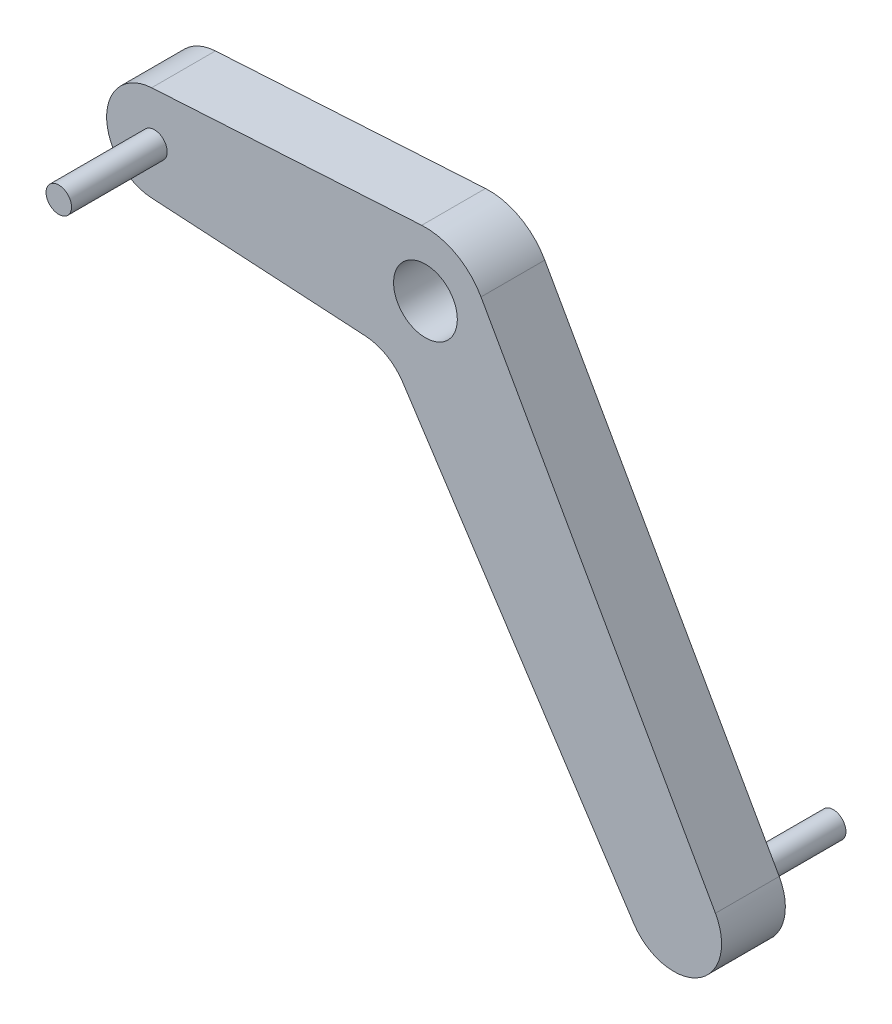
SolidWorks part; units mm, degrees
ref_plane "前视基准面" through (0, 0, 0) normal (0, 0, 1) x (1, 0, 0)
ref_plane "上视基准面" through (0, 0, 0) normal (0, 1, 0) x (1, 0, 0)
ref_plane "右视基准面" through (0, 0, 0) normal (1, 0, 0) x (0, 0, -1)
other "Configuration Table"
sketch "草图1" plane through (0, 0, 0) normal (0, 0, 1) x (1, 0, 0)
  line L0 (-85, 0) -> (0, 0) construction
  line L1 (0, 0) -> (77.8831, -128.196) construction
  line L7 (-1.1765, 19.9654) -> (-85.8824, 14.974)
  line L8 (-85.8824, -14.974) -> (-18.7635, -18.929)
  line L9 (65.3303, -136.4073) -> (-7.093, -25.6918)
  line L10 (17.4295, 9.8089) -> (90.9552, -120.8394)
  arc A5 (17.4295, 9.8089) -> (-1.1765, 19.9654) centre (0, 0) ccw
  arc A6 (-85.8824, 14.974) -> (-85.8824, -14.974) centre (-85, 0) ccw
  arc A7 (65.3303, -136.4073) -> (90.9552, -120.8394) centre (77.8831, -128.196) ccw
  arc A8 (-7.093, -25.6918) -> (-18.7635, -18.929) centre (-19.6458, -33.9031) ccw
  dimension "D1" = 15
extrude "凸台-拉伸1" add sketch "草图1" along normal blind 20
sketch "草图2" plane through (0, 0, 0) normal (0, 0, 1) x (1, 0, 0)
  circle A0 centre (0, 0) radius 10
extrude "切除-拉伸1" cut sketch "草图2" along normal blind 20
sketch "草图6" plane through (0, 0, 20) normal (0, 0, 1) x (1, 0, 0)
  circle A0 centre (-85, 0) radius 4
extrude "凸台-拉伸3" add sketch "草图6" along normal blind 30
sketch "草图7" plane through (0, 0, 0) normal (0, 0, -1) x (-1, 0, 0)
  circle A0 centre (-77.8831, -128.196) radius 4
extrude "凸台-拉伸4" add sketch "草图7" along normal blind 30
